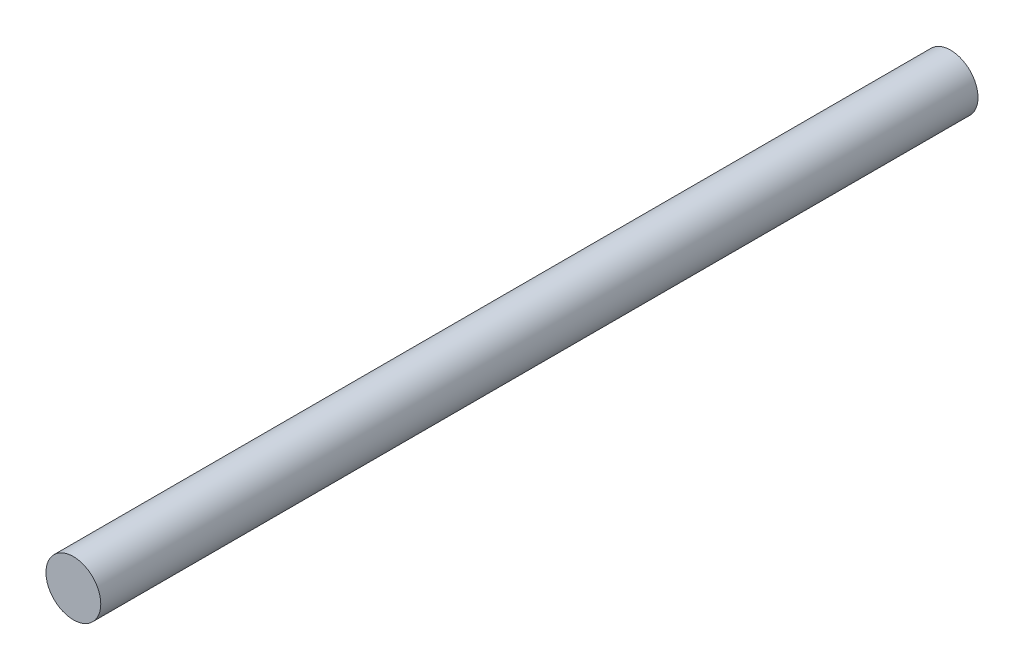
SolidWorks part; units mm, degrees
ref_plane "Front" through (0, 0, 0) normal (0, 0, 1) x (1, 0, 0)
ref_plane "Top" through (0, 0, 0) normal (0, 1, 0) x (1, 0, 0)
ref_plane "Right" through (0, 0, 0) normal (1, 0, 0) x (0, 0, -1)
sketch "Sketch1" plane through (0, 0, 0) normal (0, 0, 1) x (1, 0, 0)
  circle A0 centre (0, 0) radius 6.35
  dimension "D1" = 12.7
extrude "Boss-Extrude1" add sketch "Sketch1" along normal blind 203.2 contours A0
